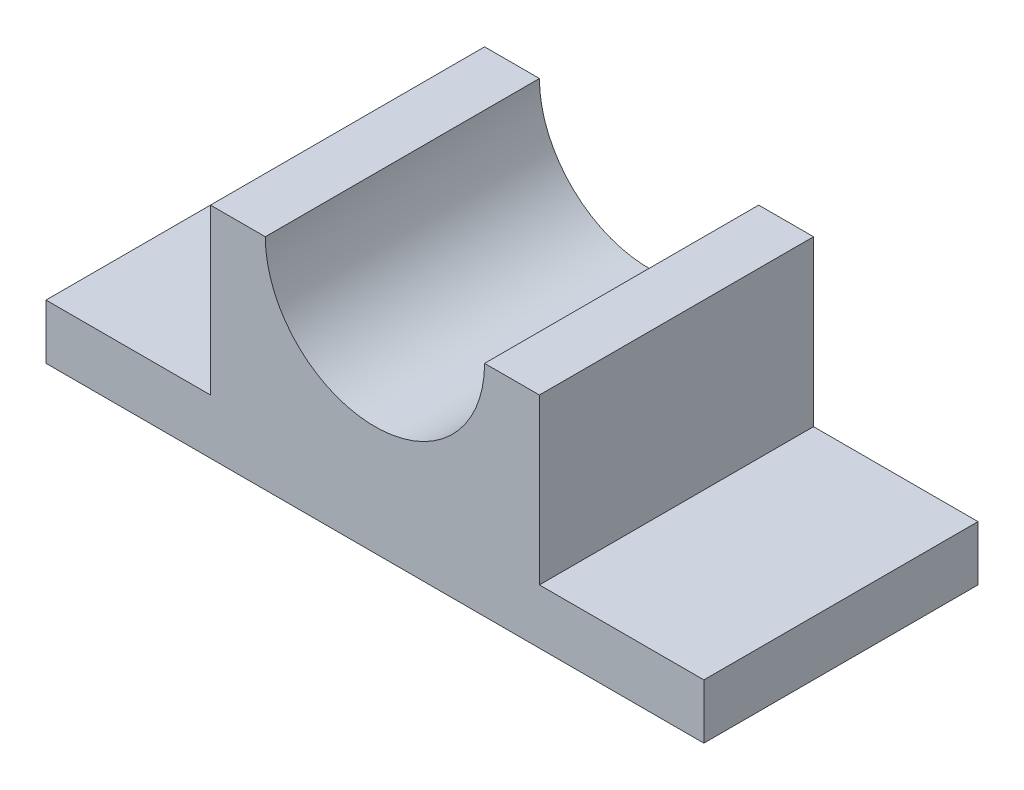
SolidWorks part; units mm, degrees
ref_plane "Front Plane" through (0, 0, 0) normal (0, 0, 1) x (1, 0, 0)
ref_plane "Top Plane" through (0, 0, 0) normal (0, 1, 0) x (1, 0, 0)
ref_plane "Right Plane" through (0, 0, 0) normal (1, 0, 0) x (0, 0, -1)
sketch "Sketch2" plane through (0, 0, 0) normal (0, 0, 1) x (1, 0, 0)
  line L0 (-25.4, 50.8) -> (-38.1, 50.8)
  line L1 (-38.1, 50.8) -> (-38.1, 12.7)
  line L2 (-38.1, 12.7) -> (-76.2, 12.7)
  line L3 (-76.2, 12.7) -> (-76.2, 0)
  line L4 (-76.2, 0) -> (76.2, 0)
  line L5 (25.4, 50.8) -> (38.1, 50.8)
  line L6 (38.1, 50.8) -> (38.1, 12.7)
  line L7 (38.1, 12.7) -> (76.2, 12.7)
  line L8 (76.2, 12.7) -> (76.2, 0)
  arc A0 (25.4, 50.8) -> (-25.4, 50.8) centre (0, 50.8) cw
  dimension "D3" = 25.4
  dimension "D1" = 12.7
  dimension "D2" = 152.4
  dimension "D4" = 76.2
  dimension "D5" = 50.8
  dimension "D6" = 38.1
extrude "Boss-Extrude1" add sketch "Sketch2" along normal mid plane 63.5
